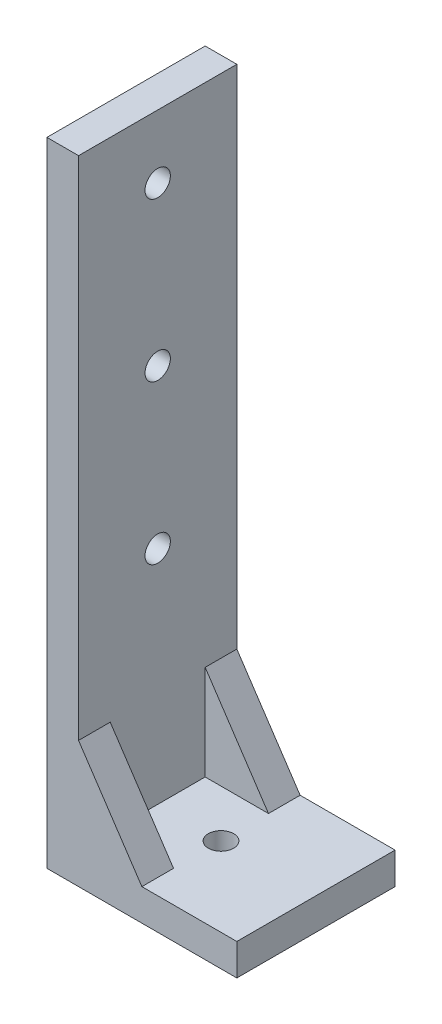
SolidWorks part; units mm, degrees
ref_plane "Front Plane" through (0, 0, 0) normal (0, 0, 1) x (1, 0, 0)
ref_plane "Top Plane" through (0, 0, 0) normal (0, 1, 0) x (1, 0, 0)
ref_plane "Right Plane" through (0, 0, 0) normal (1, 0, 0) x (0, 0, -1)
sketch "Sketch1" plane through (0, 0, 0) normal (0, 0, 1) x (1, 0, 0)
  line L0 (0, 0) -> (0, 200)
  line L1 (0, 0) -> (60, 0)
  line L2 (60, 0) -> (60, 10)
  line L3 (60, 10) -> (10, 10)
  line L4 (10, 10) -> (10, 200)
  line L5 (10, 200) -> (0, 200)
  dimension "D1" = 60
  dimension "D2" = 10
  dimension "D3" = 50
  dimension "D4" = 200
extrude "Boss-Extrude1" add sketch "Sketch1" along normal mid plane 50
sketch "Sketch2" plane through (0, 10, 0) normal (0, 1, 0) x (1, 0, 0)
  line L0 (0, 0) -> (60, 0) construction
  line L1 (60, -25) -> (60, 25) construction
  line L2 (30, 0) -> (30, 25) construction
  line L3 (60, 25) -> (10, 25) construction
  circle A0 centre (30, 0) radius 4
  dimension "D1" = 8
extrude "Cut-Extrude1" cut sketch "Sketch2" against normal through all
sketch "Sketch3" plane through (10, 0, 0) normal (1, 0, 0) x (0, 0, -1)
  line L0 (0, 0) -> (0, 200) construction
  line L1 (-25, 200) -> (25, 200) construction
  circle A0 centre (0, 180) radius 4
  circle A1 centre (0, 130) radius 4
  circle A5 centre (0, 80) radius 4
  dimension "D1" = 8
  dimension "D3" = 8
  dimension "D6" = 50
  dimension "D5" = 8
  dimension "D2" = 20
  dimension "D4" = 50
extrude "Cut-Extrude2" cut sketch "Sketch3" against normal through all
sketch "Sketch5" plane through (0, 0, 25) normal (0, 0, 1) x (1, 0, 0)
  line L0 (10, 10) -> (30, 10)
  line L1 (60, 10) -> (10, 10) construction
  line L2 (30, 10) -> (10, 40)
  line L3 (10, 10) -> (10, 200) construction
  line L4 (10, 40) -> (10, 10)
  dimension "D1" = 20
  dimension "D2" = 30
extrude "Boss-Extrude2" add sketch "Sketch5" against normal blind 10
sketch "Sketch6" plane through (0, 10, 0) normal (0, 1, 0) x (1, 0, 0)
  line L0 (0, 0) -> (60, 0) construction
  line L1 (60, -25) -> (60, 25) construction
ref_plane "Plane1" through (0, 0, 0) normal (0, 0, -1) x (-1, 0, 0)
mirror "Mirror1" about plane through (0, 0, 0) normal (0, 0, -1) of "Boss-Extrude2"
